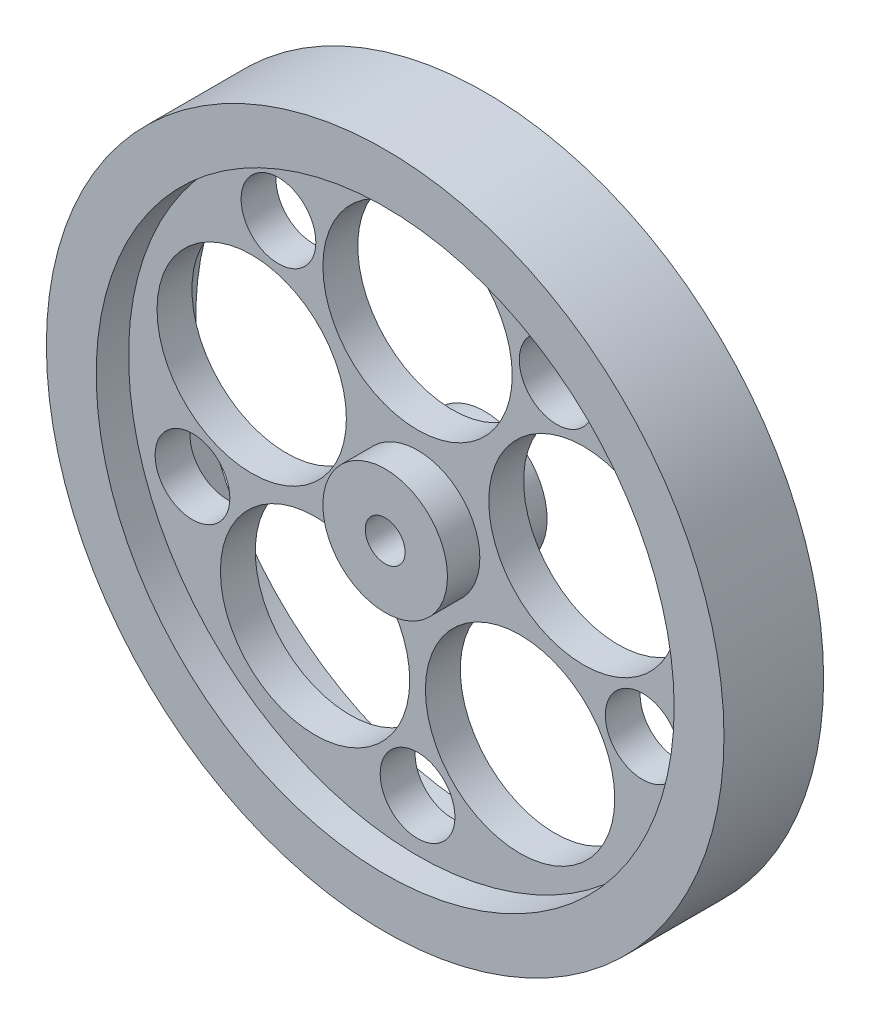
SolidWorks part; units mm, degrees
ref_plane "Front Plane" through (0, 0, 0) normal (0, 0, 1) x (1, 0, 0)
ref_plane "Top Plane" through (0, 0, 0) normal (0, 1, 0) x (1, 0, 0)
ref_plane "Right Plane" through (0, 0, 0) normal (1, 0, 0) x (0, 0, -1)
sketch "Sketch1" plane through (0, 0, 0) normal (1, 0, 0) x (0, 0, -1)
  line L0 (0, 54.4407) -> (0, -54.4407) construction
  line L1 (-10, 68) -> (10, 68)
  line L2 (10, 68) -> (10, 58)
  line L3 (10, 58) -> (3.5, 58)
  line L4 (3.5, 58) -> (3.5, 12.5)
  line L5 (3.5, 12.5) -> (10, 12.5)
  line L6 (10, 12.5) -> (10, 4)
  line L7 (10, 4) -> (-10, 4)
  line L8 (-10, 4) -> (-10, 12.5)
  line L9 (-10, 12.5) -> (-3.5, 12.5)
  line L10 (-3.5, 12.5) -> (-3.5, 58)
  line L11 (-3.5, 58) -> (-10, 58)
  line L12 (-10, 58) -> (-10, 68)
  line L13 (-51.4576, 0) -> (51.4576, 0) construction
  point P4 (0, 0)
  point P16 (0, 68)
  point P22 (0, 0)
  dimension "D1" = 4
  dimension "D2" = 12.5
  dimension "D3" = 68
  dimension "D4" = 58
revolve "Revolve1" add sketch "Sketch1" angle 360 about L13
sketch "Sketch2" plane through (0, 0, 0) normal (0, 0, 1) x (1, 0, 0)
  circle A0 centre (0, 0) radius 47.5 construction
  circle A2 centre (0, -47.5) radius 7.5
  circle A3 centre (45.1752, -14.6783) radius 7.5
  circle A4 centre (27.9198, 38.4283) radius 7.5
  circle A5 centre (-27.9198, 38.4283) radius 7.5
  circle A6 centre (-45.1752, -14.6783) radius 7.5
  circle A7 centre (0, 0) radius 35 construction
  circle A8 centre (0, 35) radius 19
  circle A9 centre (0.0007, 0.001) radius 35 construction
  circle A10 centre (33.2877, 10.8165) radius 19
  circle A11 centre (0.0018, 0.0006) radius 35 construction
  circle A12 centre (20.5743, -28.315) radius 19
  circle A13 centre (0.0018, -0.0006) radius 35 construction
  circle A14 centre (-20.5707, -28.3162) radius 19
  circle A15 centre (0.0007, -0.001) radius 35 construction
  circle A16 centre (-33.2863, 10.8146) radius 19
  point P15 (0, 0)
  point P35 (0.001, 0)
  dimension "D1" = 5
  dimension "D2" = 15
  dimension "D4" = 70
  dimension "D5" = 38
  dimension "D6" = 95
  dimension "D7" = 0.0007
  dimension "D3" = 5
extrude "Cut-Extrude1" cut sketch "Sketch2" against normal through all both and the other way through all
